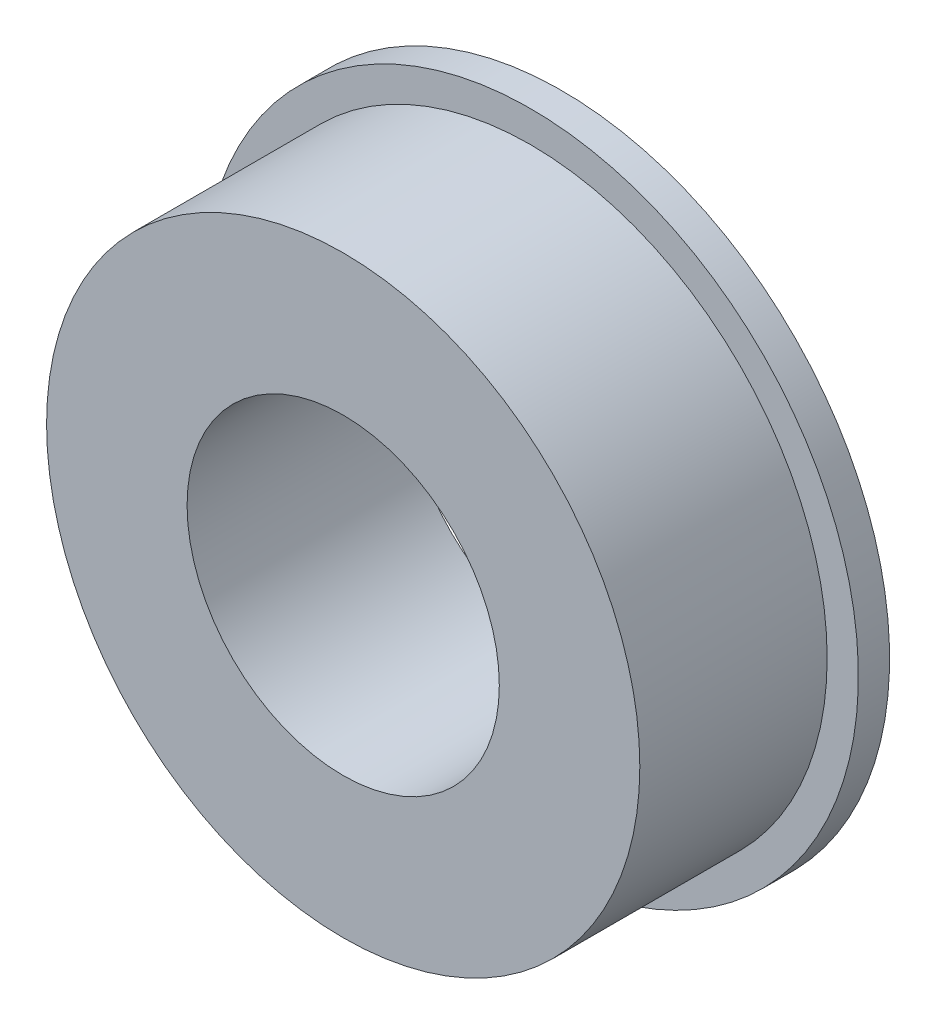
SolidWorks part; units mm, degrees
ref_plane "前视基准面" through (0, 0, 0) normal (0, 0, 1) x (1, 0, 0)
ref_plane "上视基准面" through (0, 0, 0) normal (0, 1, 0) x (1, 0, 0)
ref_plane "右视基准面" through (0, 0, 0) normal (1, 0, 0) x (0, 0, -1)
sketch "草图1" plane through (0, 0, 0) normal (0, 0, 1) x (1, 0, 0)
  circle A0 centre (0, 0) radius 9.5
  circle A1 centre (0, 0) radius 5
  dimension "D1" = 10
  dimension "D2" = 19
extrude "凸台-拉伸1" add sketch "草图1" along normal blind 6 separate body
sketch "草图2" plane through (0, 0, 0) normal (0, 0, -1) x (-1, 0, 0)
  circle A0 centre (0, 0) radius 5
  circle A1 centre (0, 0) radius 10.5
  dimension "D1" = 21
extrude "凸台-拉伸2" add sketch "草图2" along normal blind 1
